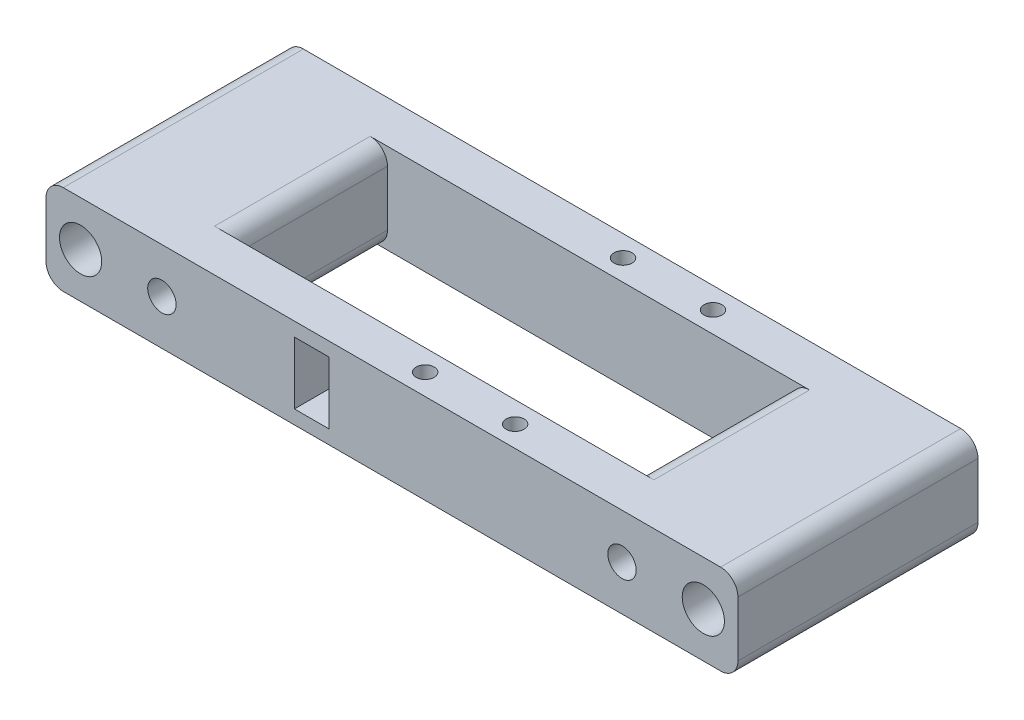
SolidWorks part; units mm, degrees
ref_plane "Front Plane" through (0, 0, 0) normal (0, 0, 1) x (1, 0, 0)
ref_plane "Top Plane" through (0, 0, 0) normal (0, 1, 0) x (1, 0, 0)
ref_plane "Right Plane" through (0, 0, 0) normal (1, 0, 0) x (0, 0, -1)
sketch "Sketch1" plane through (0, 0, 0) normal (0, 0, 1) x (1, 0, 0)
  line L0 (-58.5, 26) -> (-58.5, 0) construction
  line L1 (0, 0) -> (-100, 0)
  line L2 (0, 0) -> (0, 26)
  line L3 (0, 26) -> (-100, 26)
  line L4 (-100, 0) -> (-100, 26)
  circle A0 centre (-90, 13) radius 6.1
  circle A1 centre (-66.5, 13) radius 4.1
  point P9 (-100, 13)
  dimension "D3" = 12.2
  dimension "D4" = 8.2
  dimension "D1" = 100
  dimension "D2" = 26
  dimension "D5" = 23.5
  dimension "D6" = 10
  dimension "D7" = 8
  dimension "D8" = 41.5
extrude "Boss-Extrude1" add sketch "Sketch1" along normal blind 40
sketch "Sketch2" plane through (0, 0, 0) normal (0, 0, -1) x (-1, 0, 0)
  line L1 (100, 26) -> (0, 26)
  line L2 (100, 26) -> (100, 0)
  line L3 (100, 0) -> (0, 0)
  line L4 (0, 26) -> (0, 0)
extrude "Boss-Extrude2" add sketch "Sketch2" along normal blind 29.4
sketch "Sketch3" plane through (0, 26, 0) normal (0, 1, 0) x (1, 0, 0)
  line L0 (0, -40) -> (0, 29.4) construction
  line L1 (0, 17.2) -> (-58.5, 17.2)
  line L2 (0, 17.2) -> (0, -27.8)
  line L3 (0, -27.8) -> (-58.5, -27.8)
  line L4 (-58.5, 17.2) -> (-58.5, -27.8)
  line L5 (-100, -40) -> (-100, 29.4) construction
  line L6 (-100, 29.4) -> (0, 29.4) construction
  line L7 (0, -40) -> (-100, -40) construction
  dimension "D1" = 41.5
  dimension "D2" = 12.2
  dimension "D3" = 12.2
extrude "Cut-Extrude1" cut sketch "Sketch3" against normal up to next
mirror "Mirror2" about plane through (0, 0, 40) normal (-1, 0, 0) of "Boss-Extrude2", "Cut-Extrude1", "Boss-Extrude1"
sketch "Sketch4" plane through (0, 26, 0) normal (0, 1, 0) x (1, 0, 0)
  line L0 (-100, 29.4) -> (100, 29.4) construction
  line L1 (-5.5, 29.4) -> (-5.5, 17.2) construction
  line L2 (58.5, 17.2) -> (-58.5, 17.2) construction
  line L3 (58.5, 17.2) -> (58.5, -27.8) construction
  circle A0 centre (3.5, 23.3) radius 2.6
  circle A1 centre (29.5, 23.3) radius 2.6
  dimension "D1" = 6.1
  dimension "D3" = 9
  dimension "D4" = 26
  dimension "D5" = 5.2
  dimension "D2" = 64
extrude "Cut-Extrude2" cut sketch "Sketch4" against normal through all
sketch "Sketch5" plane through (0, 0, 0) normal (0, -1, 0) x (1, 0, 0)
  line L1 (34.2343, -23.3) -> (31.8671, -19.2)
  line L2 (31.8671, -19.2) -> (27.1329, -19.2)
  line L3 (27.1329, -19.2) -> (24.7657, -23.3)
  line L4 (24.7657, -23.3) -> (27.1329, -27.4)
  line L5 (27.1329, -27.4) -> (31.8671, -27.4)
  line L6 (31.8671, -27.4) -> (34.2343, -23.3)
  line L7 (-1.2343, -23.3) -> (1.1329, -27.4)
  line L8 (1.1329, -27.4) -> (5.8671, -27.4)
  line L9 (5.8671, -27.4) -> (8.2343, -23.3)
  line L10 (8.2343, -23.3) -> (5.8671, -19.2)
  line L11 (5.8671, -19.2) -> (1.1329, -19.2)
  line L12 (1.1329, -19.2) -> (-1.2343, -23.3)
  circle A0 centre (29.5, -23.3) radius 4.1 construction
  circle A1 centre (3.5, -23.3) radius 4.1 construction
  dimension "D1" = 8.2
  dimension "D2" = 8.2
extrude "Cut-Extrude3" cut sketch "Sketch5" against normal blind 4
ref_plane "Plane1" through (0, 0, 5.3) normal (0, 0, 1) x (1, 0, 0)
mirror "Mirror3" about plane through (0, 0, 5.3) normal (0, 0, 1) of "Cut-Extrude3", "Cut-Extrude2"
sketch "Sketch6" plane through (0, 0, 40) normal (0, 0, 1) x (1, 0, 0)
  line L0 (-8.1, 26) -> (-8.1, 0) construction
  line L1 (100, 26) -> (-100, 26) construction
  line L2 (-100, 0) -> (100, 0) construction
  line L3 (0.9, 26) -> (0.9, 4) construction
  line L4 (-100, 26) -> (-100, 0) construction
  line L5 (-18.2, 22) -> (-28.2, 22)
  line L6 (-18.2, 22) -> (-18.2, 4)
  line L7 (-18.2, 4) -> (-28.2, 4)
  line L8 (-28.2, 22) -> (-28.2, 4)
  point P12 (-28.2, 13)
  point P15 (-100, 13)
  dimension "D1" = 9
  dimension "D2" = 10.1
  dimension "D3" = 10
  dimension "D4" = 18
extrude "Cut-Extrude4" cut sketch "Sketch6" against normal up to vertex (12.2 mm away) up to point (-58.5, 26, 27.8)
fillet "Fillet1" radius 5 8 edges at (58.5, 26, 5.3) (58.5, 0, 5.3) (-58.5, 0, 5.3) (100, 0, 5.3) (100, 26, 5.3) (-100, 0, 5.3) (-100, 26, 5.3) (-58.5, 26, 5.3)
